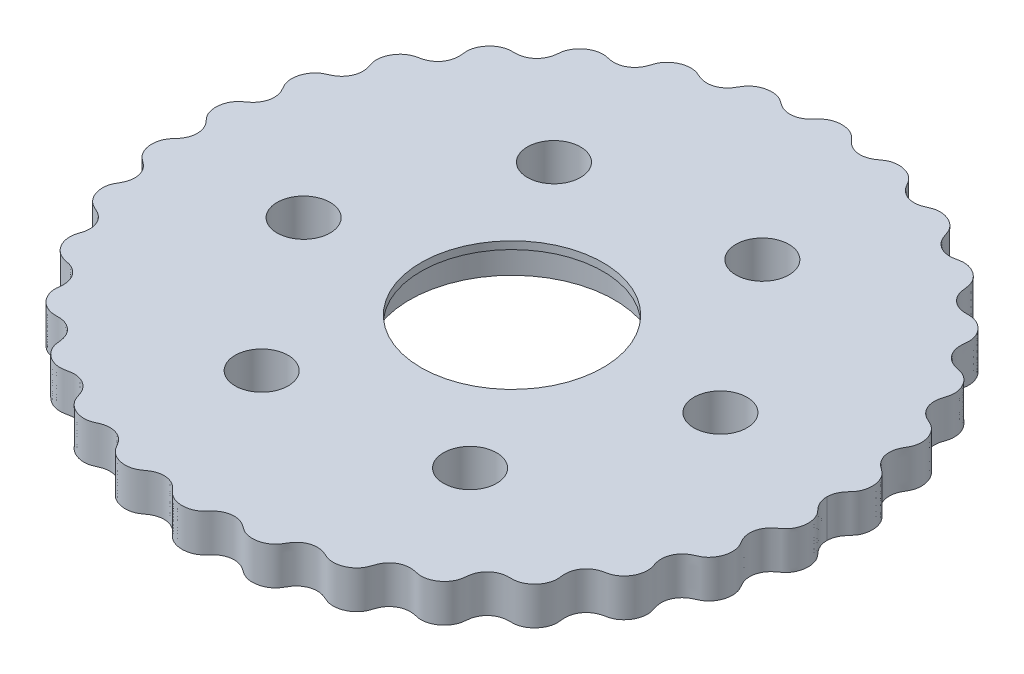
SolidWorks part; units mm, degrees
ref_plane "Front Plane" through (0, 0, 0) normal (0, 0, 1) x (1, 0, 0)
ref_plane "Top Plane" through (0, 0, 0) normal (0, 1, 0) x (1, 0, 0)
ref_plane "Right Plane" through (0, 0, 0) normal (1, 0, 0) x (0, 0, -1)
sketch "Sketch1" plane through (0, 0, 0) normal (0, 1, 0) x (1, 0, 0)
  line L0 (1, 0) -> (26, 0) construction
  line L1 (1, 0) -> (25.863, 2.6132) construction
  circle A0 centre (1, 0) radius 13.5
  circle A1 centre (11.1684, 22.8386) radius 3.5
  circle A2 centre (25.863, 2.6132) radius 3.5
  circle A3 centre (-13.6946, 20.2254) radius 3.5
  circle A4 centre (-23.863, -2.6132) radius 3.5
  circle A5 centre (-9.1684, -22.8386) radius 3.5
  circle A6 centre (15.6946, -20.2254) radius 3.5
  circle A7 centre (1, 0) radius 25 construction
  spline S0 degree 3 number of poles 1508 (-40.5029, 0.0721) -> (42.5, 0)
  spline S1 degree 3 number of poles 1509 (42.5, 0) -> (-40.5029, 0.0721)
  point P20 (1, 0)
  dimension "D2" = 7
  dimension "D3" = 6
  dimension "D1" = 6
extrude "Boss-Extrude1" add sketch "Sketch1" along normal blind 5
sketch "Sketch2" plane through (0, 5, 0) normal (0, 1, 0) x (1, 0, 0)
  circle A0 centre (1, 0) radius 13.5
  circle A1 centre (1, 0) radius 12
  dimension "D1" = 24
extrude "Boss-Extrude2" add sketch "Sketch2" against normal blind 1
